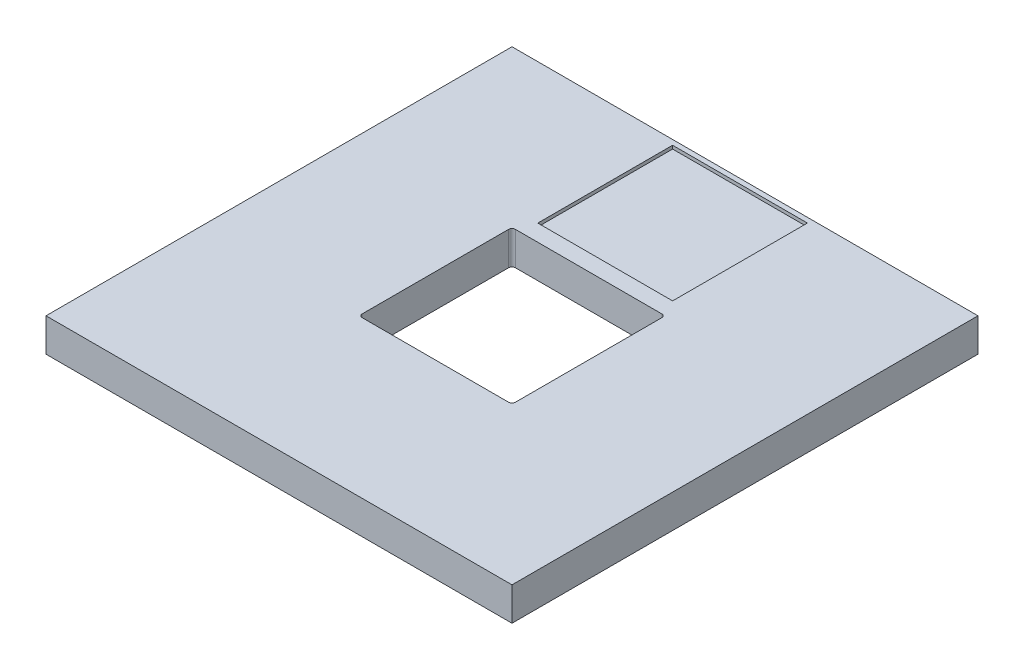
SolidWorks part; units mm, degrees
ref_plane "Ebene vorne" through (0, 0, 0) normal (0, 0, 1) x (1, 0, 0)
ref_plane "Ebene oben" through (0, 0, 0) normal (0, 1, 0) x (1, 0, 0)
ref_plane "Ebene rechts" through (0, 0, 0) normal (1, 0, 0) x (0, 0, -1)
sketch "Skizze1" plane through (0, 0, 0) normal (0, 1, 0) x (1, 0, 0)
  line L0 (70, 269.794) -> (70, -57.286) construction
  line L1 (0, 0) -> (140, 0)
  line L2 (0, 0) -> (0, 140)
  line L3 (0, 140) -> (140, 140)
  line L4 (140, 0) -> (140, 140)
  line L5 (-110.335, 70) -> (261.8333, 70) construction
  line L7 (47, 93) -> (93, 93)
  line L8 (47, 93) -> (47, 47)
  line L9 (47, 47) -> (93, 47)
  line L10 (93, 93) -> (93, 47)
  point P8 (70, 93)
  point P10 (47, 70)
  point P11 (70, 140)
  point P12 (0, 70)
  dimension "D1" = 140
  dimension "D2" = 140
  dimension "D3" = 46
  dimension "D5" = 46
extrude "Aufsatz-Linear austragen1" add sketch "Skizze1" along normal blind 10
sketch "Skizze3" plane through (0, 10, 0) normal (0, 1, 0) x (1, 0, 0)
  line L0 (93, 93) -> (47, 93) construction
  line L1 (47, 93) -> (47, 47) construction
  line L2 (49.75, 138.5) -> (90.25, 138.5)
  line L3 (49.75, 138.5) -> (49.75, 98)
  line L4 (49.75, 98) -> (90.25, 98)
  line L5 (90.25, 138.5) -> (90.25, 98)
  line L8 (70, 162.5869) -> (70, 41.5515) construction
  point P14 (70, 138.5)
  point P15 (70, 102.0692)
  point P16 (70, 93)
  dimension "D1" = 40.5
  dimension "D2" = 40.5
  dimension "D3" = 5
extrude "Schnitt-Linear austragen1" cut sketch "Skizze3" against normal blind 1 contours L3 L2 L5 L4
fillet "Verrundung1" radius 1 4 edges at (93, 5, -47) (47, 5, -47) (93, 5, -93) (47, 5, -93)
